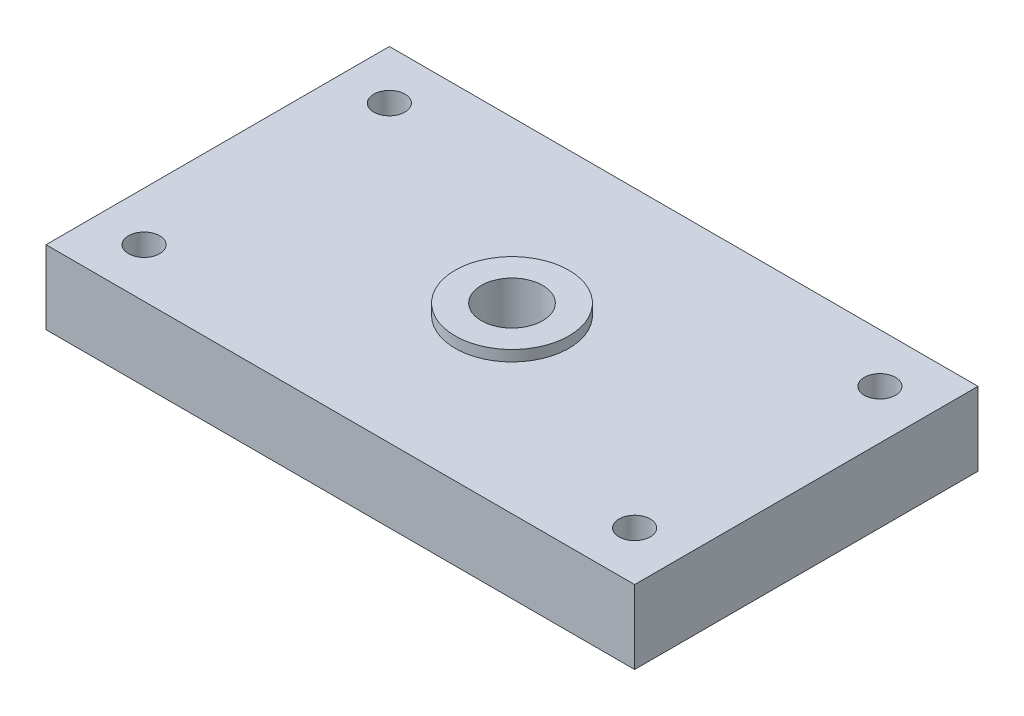
SolidWorks part; units mm, degrees
material "6061-T6 (SS)"
ref_plane "Front Plane" through (0, 0, 0) normal (0, 0, 1) x (1, 0, 0)
ref_plane "Top Plane" through (0, 0, 0) normal (0, 1, 0) x (1, 0, 0)
ref_plane "Right Plane" through (0, 0, 0) normal (1, 0, 0) x (0, 0, -1)
sketch "Sketch1" plane through (0, 0, 0) normal (0, 1, 0) x (1, 0, 0)
  line L1 (0, 0) -> (76.2, 0)
  line L2 (0, 0) -> (0, 44.45)
  line L3 (0, 44.45) -> (76.2, 44.45)
  line L4 (76.2, 0) -> (76.2, 44.45)
  dimension "D1" = 44.45
  dimension "D2" = 76.2
extrude "Boss-Extrude1" add sketch "Sketch1" along normal blind 9.525
hole_wizard "#10-32 Tapped Hole1" positions "Sketch4" profile "Sketch3" tap size "#10-32" standard "Ansi Inch" end condition through all
sketch "Sketch4" plane through (0, 9.525, 0) normal (0, 1, 0) x (-1, 0, 0)
  line L0 (-38.1, -44.45) -> (-38.1, 0) construction
  line L1 (-76.2, -44.45) -> (0, -44.45) construction
  line L2 (0, 0) -> (-76.2, 0) construction
  line L4 (0, -22.225) -> (-76.2, -22.225) construction
  line L5 (0, -44.45) -> (0, 0) construction
  line L6 (-76.2, 0) -> (-76.2, -44.45) construction
  point P0 (-6.35, -38.1)
  point P1 (-69.85, -38.1)
  point P3 (-69.85, -6.35)
  point P5 (-6.35, -6.35)
  dimension "D1" = 15.875
  dimension "D2" = 15.875
  dimension "D3" = 31.75
  dimension "D4" = 31.75
sketch "Sketch3" plane through (6.35, 9.525, -38.1) normal (1, 0, 0) x (0, 0, 1)
  line L0 (0, 0) -> (0, 9.525)
  line L1 (0, 9.525) -> (2.0193, 9.525)
  line L2 (2.0193, 9.525) -> (2.0193, 0)
  line L5 (2.0193, 0) -> (0, 0)
  line L11 (0, -6.35) -> (0, 107.95) construction
  dimension "Thru Tap Drill Dia." = 4.0386
  dimension "Thru Tap Drill Depth" = 9.525
cosmetic thread "Hole Thread1" parameters "D2"=4.826
cosmetic thread "Hole Thread2" parameters "D2"=4.826
cosmetic thread "Hole Thread3" parameters "D2"=4.826
cosmetic thread "Hole Thread4" parameters "D2"=4.826
sketch "Sketch9" plane through (0, 9.525, 0) normal (0, 1, 0) x (1, 0, 0)
  line L0 (0, 22.225) -> (76.2, 22.225) construction
  line L1 (0, 44.45) -> (0, 0) construction
  line L2 (76.2, 0) -> (76.2, 44.45) construction
  circle A0 centre (38.1, 22.225) radius 7.366
  dimension "D1" = 14.732
extrude "Boss-Extrude2" add sketch "Sketch9" along normal blind 1.397
hole_wizard "3/8-16 Tapped Hole1" positions "Sketch11" profile "Sketch12" tap size "3/8-16" standard "Ansi Inch" end condition up to next
sketch "Sketch11" plane through (0, 10.922, 0) normal (0, 1, 0) x (-1, 0, 0)
  point P0 (-38.1, -22.225)
sketch "Sketch12" plane through (38.1, 10.922, -22.225) normal (1, 0, 0) x (0, 0, 1)
  line L0 (0, 0) -> (0, 10.922)
  line L1 (0, 10.922) -> (3.9687, 10.922)
  line L2 (3.9687, 10.922) -> (3.9687, 0)
  line L5 (3.9687, 0) -> (0, 0)
  line L11 (0, -6.35) -> (0, 107.95) construction
  dimension "Thru Tap Drill Dia." = 7.9375
  dimension "Thru Tap Drill Depth" = 10.922
cosmetic thread "Hole Thread5" parameters "D2"=9.525
